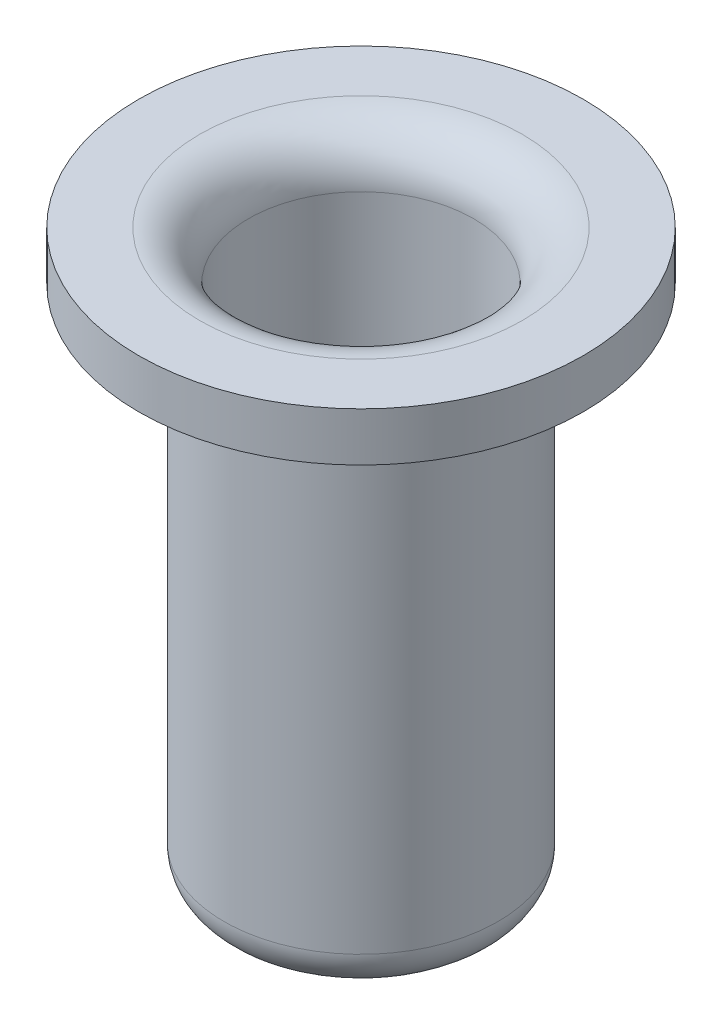
SolidWorks part; units mm, degrees
material "Glass"
ref_plane "Front" through (0, 0, 0) normal (0, 0, 1) x (1, 0, 0)
ref_plane "Top" through (0, 0, 0) normal (0, 1, 0) x (1, 0, 0)
ref_plane "Right" through (0, 0, 0) normal (1, 0, 0) x (0, 0, -1)
sketch "Sketch1" plane through (0, 0, 0) normal (0, 0, 1) x (1, 0, 0)
  line L0 (0, 0) -> (0, 94) construction
  line L1 (22.5, 86) -> (22.5, 6.5)
  line L2 (0, 0) -> (16, 0)
  line L3 (22.5, 86) -> (36.5, 86)
  line L4 (36.5, 86) -> (36.5, 94)
  line L5 (36.5, 94) -> (18.5, 94)
  line L6 (18.5, 94) -> (18.5, 6.5)
  line L7 (16, 4) -> (0, 4)
  line L8 (0, 4) -> (0, 0)
  arc A0 (16, 0) -> (22.5, 6.5) centre (16, 6.5) ccw
  arc A1 (18.5, 6.5) -> (16, 4) centre (16, 6.5) cw
  dimension "D6" = 6.5
  dimension "D1" = 4
  dimension "D2" = 45
  dimension "D3" = 90
  dimension "D4" = 8
  dimension "D5" = 14
revolve "Revolve1" add sketch "Sketch1" angle 360 about L0
fillet "Fillet1" radius 4 1 edges at (0, 86, -22.5)
fillet "Fillet2" radius 8 1 edges at (0, 94, -18.5)
